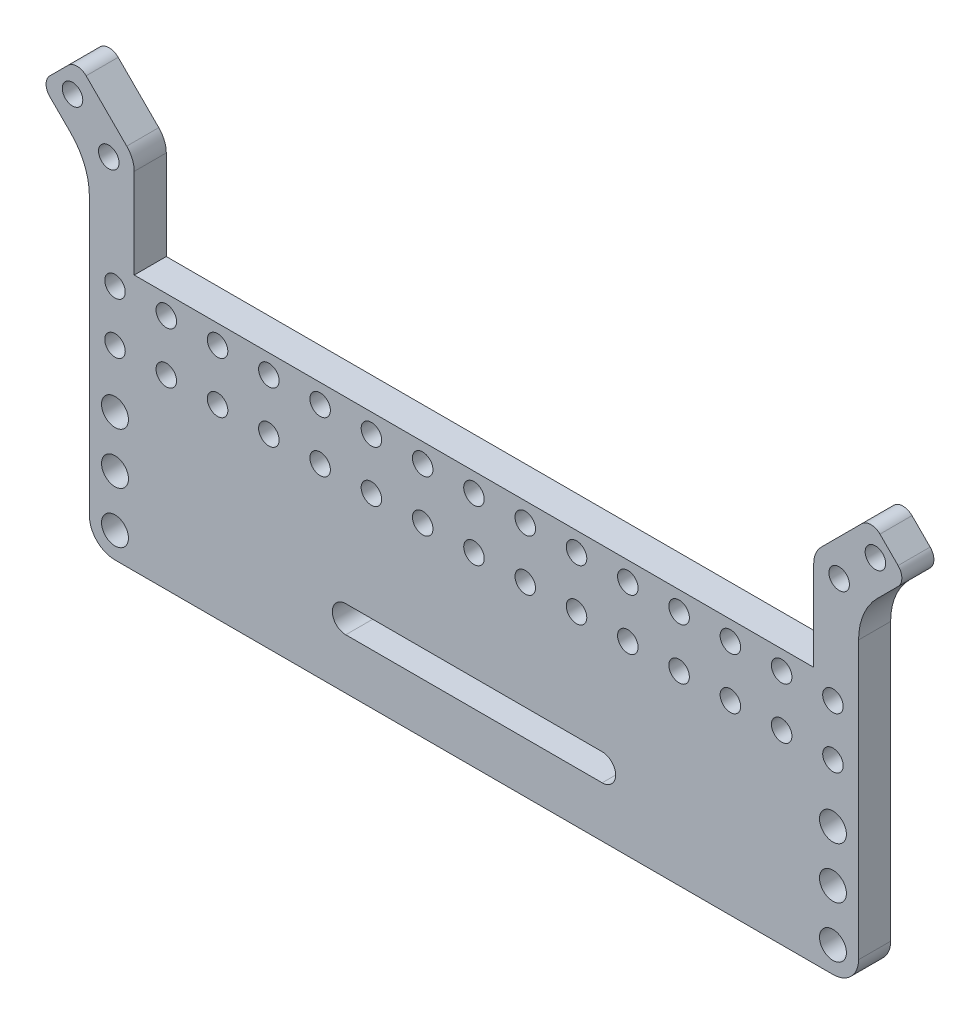
SolidWorks part; units mm, degrees
ref_plane "前视基准面" through (0, 0, 0) normal (0, 0, 1) x (1, 0, 0)
ref_plane "上视基准面" through (0, 0, 0) normal (0, 1, 0) x (1, 0, 0)
ref_plane "右视基准面" through (0, 0, 0) normal (1, 0, 0) x (0, 0, -1)
sketch "草图2" plane through (0, 0, 0) normal (0, 0, 1) x (1, 0, 0)
  line L0 (-56, 17) -> (-48, 17) construction
  line L1 (-53, 20) -> (53, 20)
  line L2 (-60, 20) -> (-60, -20)
  line L3 (-60, -20) -> (60, -20)
  line L4 (60, 20) -> (60, -20)
  line L5 (-60, 20) -> (60, -20) construction
  line L6 (-60, -20) -> (60, 20) construction
  line L7 (667.1068, -690.1068) -> (-34688.2323, 34665.2323) construction
  line L8 (-40, 17) -> (-62.6274, 39.6274) construction
  line L9 (-60, 20) -> (-53, 20) construction
  line L10 (0, -55) -> (0, 55) construction
  line L11 (-61.9203, 44.5772) -> (-67.5772, 38.9203)
  line L12 (-60, 20) -> (-60, 31.3431)
  line L13 (-53, 20) -> (-53, 35.6569)
  line L14 (-60, 31.3431) -> (-67.5772, 38.9203)
  line L15 (-53, 35.6569) -> (-61.9203, 44.5772)
  line L16 (53, 20) -> (53, 35.6569)
  line L17 (53, 35.6569) -> (61.9203, 44.5772)
  line L18 (61.9203, 44.5772) -> (67.5772, 38.9203)
  line L19 (60, 31.3431) -> (67.5772, 38.9203)
  line L20 (60, 20) -> (60, 31.3431)
  line L21 (53, 20) -> (60, 20) construction
  line L22 (-56, 17) -> (-56, 9) construction
  line L23 (-56, -16) -> (-56, -8) construction
  line L24 (-20, -10) -> (20, -10) construction
  line L25 (-20, -7.9) -> (20, -7.9)
  line L26 (-20, -12.1) -> (20, -12.1)
  line L27 (-62.6274, 39.6274) -> (-56.9706, 33.9706) construction
  circle A0 centre (-56, 17) radius 1.6
  circle A1 centre (-48, 17) radius 1.6
  circle A2 centre (-40, 17) radius 1.6
  circle A3 centre (-32, 17) radius 1.6
  circle A4 centre (-24, 17) radius 1.6
  circle A5 centre (-16, 17) radius 1.6
  circle A6 centre (-8, 17) radius 1.6
  circle A7 centre (0, 17) radius 1.6
  circle A8 centre (8, 17) radius 1.6
  circle A9 centre (16, 17) radius 1.6
  circle A10 centre (24, 17) radius 1.6
  circle A11 centre (32, 17) radius 1.6
  circle A12 centre (40, 17) radius 1.6
  circle A13 centre (48, 17) radius 1.6
  circle A14 centre (56, 17) radius 1.6
  circle A15 centre (-62.6274, 39.6274) radius 1.6
  circle A16 centre (62.6274, 39.6274) radius 1.6
  circle A17 centre (-56, 9) radius 1.6
  circle A18 centre (-48, 9) radius 1.6
  circle A19 centre (-40, 9) radius 1.6
  circle A20 centre (-32, 9) radius 1.6
  circle A21 centre (-24, 9) radius 1.6
  circle A22 centre (-16, 9) radius 1.6
  circle A23 centre (-8, 9) radius 1.6
  circle A24 centre (0, 9) radius 1.6
  circle A25 centre (8, 9) radius 1.6
  circle A26 centre (16, 9) radius 1.6
  circle A27 centre (24, 9) radius 1.6
  circle A28 centre (32, 9) radius 1.6
  circle A29 centre (40, 9) radius 1.6
  circle A30 centre (48, 9) radius 1.6
  circle A31 centre (56, 9) radius 1.6
  circle A32 centre (-56, -16) radius 2.1
  circle A33 centre (-56, -8) radius 2.1
  circle A34 centre (-56, 0) radius 2.1
  circle A35 centre (56, -16) radius 2.1
  circle A36 centre (56, -8) radius 2.1
  circle A37 centre (56, 0) radius 2.1
  arc A38 (-20, -7.9) -> (-20, -12.1) centre (-20, -10) ccw
  arc A39 (20, -12.1) -> (20, -7.9) centre (20, -10) ccw
  circle A40 centre (-56.9706, 33.9706) radius 1.6
  circle A41 centre (56.9706, 33.9706) radius 1.6
  point P0 (0, 0)
  point P105 (0, -10)
  dimension "D3" = 3.2
  dimension "D9" = 2
  dimension "D20" = 4
  dimension "D21" = 4.2
  dimension "D26" = 2.1
  dimension "D1" = 120
  dimension "D2" = 40
  dimension "D4" = 3
  dimension "D5" = 4
  dimension "D7" = 8
  dimension "D8" = 45
  dimension "D10" = 32
  dimension "D11" = 3
  dimension "D12" = 3
  dimension "D13" = 4
  dimension "D14" = 4
  dimension "D15" = 4
  dimension "D17" = 8
  dimension "D18" = 90
  dimension "D19" = 4
  dimension "D23" = 8
  dimension "D24" = 10
  dimension "D25" = 20
  dimension "D28" = 8
  dimension "D6" = 15
  dimension "D16" = 2
  dimension "D22" = 3
  dimension "D27" = 2
extrude "凸台-拉伸3" add sketch "草图2" along normal blind 5
fillet "圆角1" radius 4 4 edges at (-60, -20, 2.5) (60, -20, 2.5) (53, 35.6569, 2.5) (-53, 35.6569, 2.5)
fillet "圆角2" radius 10 2 edges at (60, 31.3431, 2.5) (-60, 31.3431, 2.5)
fillet "圆角3" radius 2 4 edges at (61.9203, 44.5772, 2.5) (67.5772, 38.9203, 2.5) (-61.9203, 44.5772, 2.5) (-67.5772, 38.9203, 2.5)
